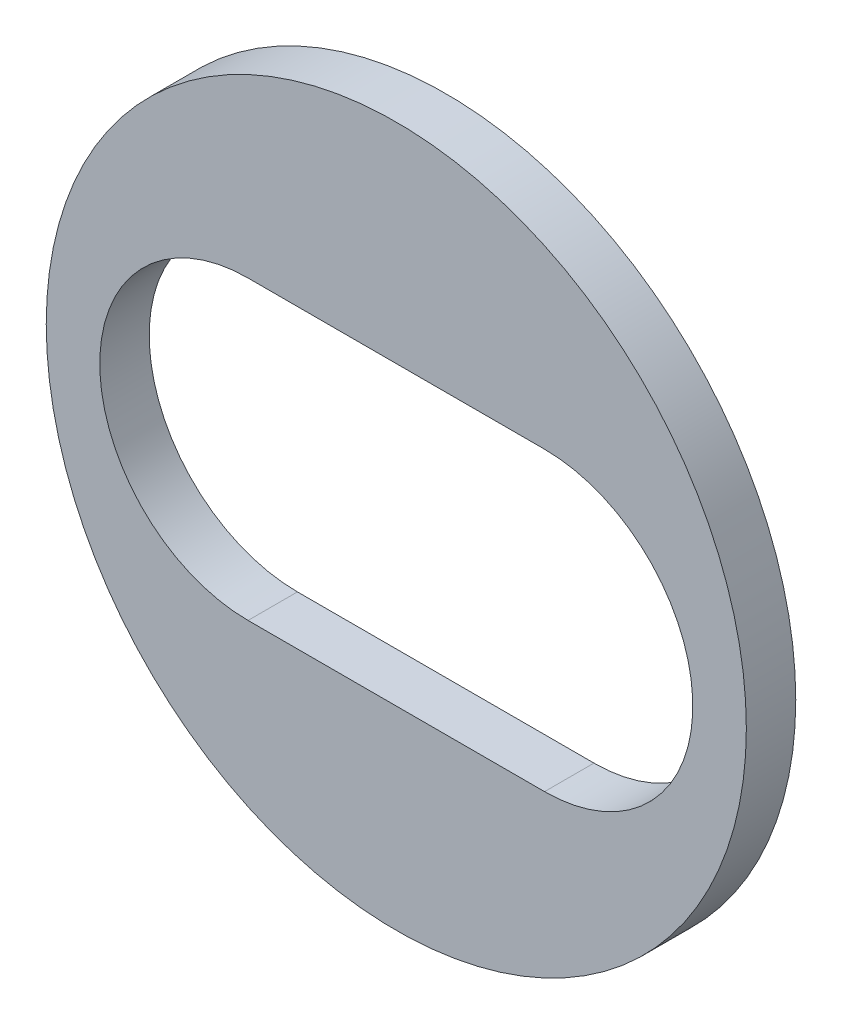
SolidWorks part; units mm, degrees
ref_plane "Plan de face" through (0, 0, 0) normal (0, 0, 1) x (1, 0, 0)
ref_plane "Plan de dessus" through (0, 0, 0) normal (0, 1, 0) x (1, 0, 0)
ref_plane "Plan de droite" through (0, 0, 0) normal (1, 0, 0) x (0, 0, -1)
sketch "Esquisse1" plane through (0, 0, 0) normal (0, 0, 1) x (1, 0, 0)
  line L0 (0, 0) -> (42.5, 0) construction
  circle A0 centre (0, 0) radius 42.5
  dimension "D1" = 42.5
extrude "Boss.-Extru.1" add sketch "Esquisse1" along normal blind 6
sketch "Esquisse3" plane through (0, 0, 0) normal (0, 0, 1) x (1, 0, 0)
  line L0 (-18, -18.9) -> (18, -18.9)
  line L4 (18, 17.1) -> (-18, 17.1)
  arc A0 (18, -18.9) -> (18, 17.1) centre (18, -0.9) ccw
  arc A3 (-18, 17.1) -> (-18, -18.9) centre (-18, -0.9) ccw
  point P4 (0, 0)
  point P6 (0, -0.9)
  point P18 (0, -0.9)
  dimension "D1" = 18
  dimension "D2" = 36
  dimension "D3" = 2
  dimension "D4" = 36
  dimension "D5" = 18
extrude "Enlèv. mat.-Extru.6" cut sketch "Esquisse3" against normal blind 6 and the other way through all
